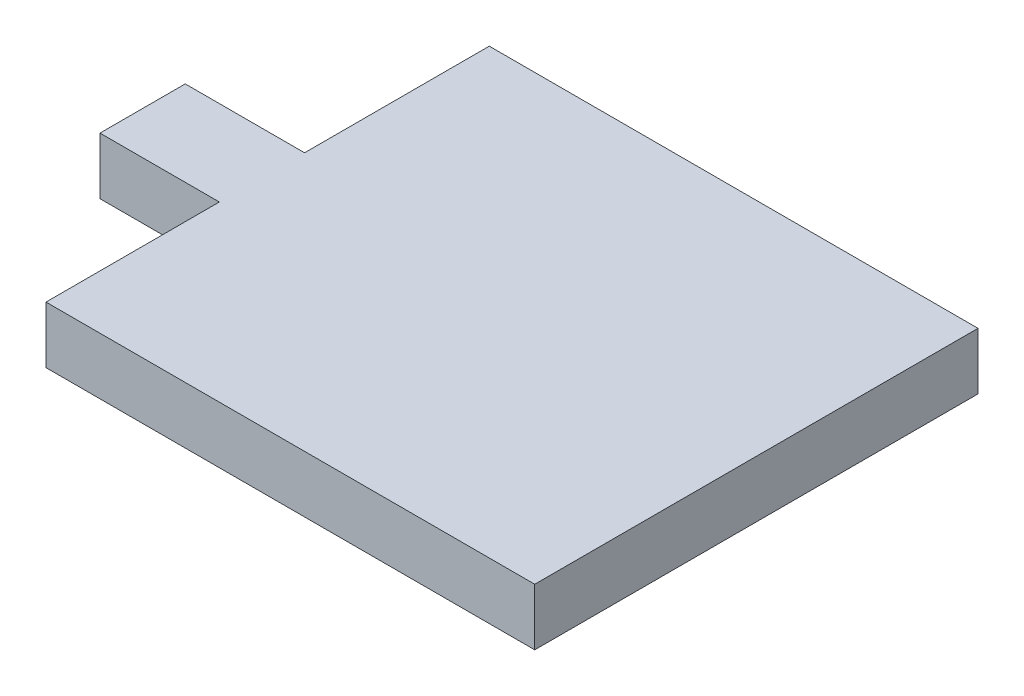
SolidWorks part; units mm, degrees
ref_plane "Front Plane" through (0, 0, 0) normal (0, 0, 1) x (1, 0, 0)
ref_plane "Top Plane" through (0, 0, 0) normal (0, 1, 0) x (1, 0, 0)
ref_plane "Right Plane" through (0, 0, 0) normal (1, 0, 0) x (0, 0, -1)
sketch "Sketch1" plane through (0, 0, 0) normal (0, 1, 0) x (1, 0, 0)
  line L0 (0, 22.75) -> (-10.5, 22.75)
  line L1 (0, 0) -> (43, 0)
  line L2 (0, 0) -> (0, 15.25)
  line L3 (0, 39) -> (43, 39)
  line L4 (43, 0) -> (43, 39)
  line L5 (-10.5, 22.75) -> (-10.5, 15.25)
  line L6 (-10.5, 15.25) -> (0, 15.25)
  line L8 (0, 22.75) -> (0, 39)
  dimension "D1" = 39
  dimension "D2" = 43
  dimension "D3" = 7.5
  dimension "D4" = 10.5
  dimension "D5" = 16.25
extrude "Boss-Extrude1" add sketch "Sketch1" along normal blind 5
sketch "Sketch3" plane through (-10.5, 0, 0) normal (-1, 0, 0) x (0, 0, 1)
  line L0 (-22.75, 5) -> (-22.75, 0) construction
  line L1 (-21.5, 3.5) -> (-16.5, 3.5)
  line L2 (-21.5, 3.5) -> (-21.5, 1.5)
  line L3 (-21.5, 1.5) -> (-16.5, 1.5)
  line L4 (-16.5, 3.5) -> (-16.5, 1.5)
  line L5 (-22.75, 5) -> (-15.25, 5) construction
  dimension "D1" = 2
  dimension "D2" = 5
  dimension "D3" = 1.25
  dimension "D4" = 1.5
extrude "Cut-Extrude1" cut sketch "Sketch3" against normal blind 14
